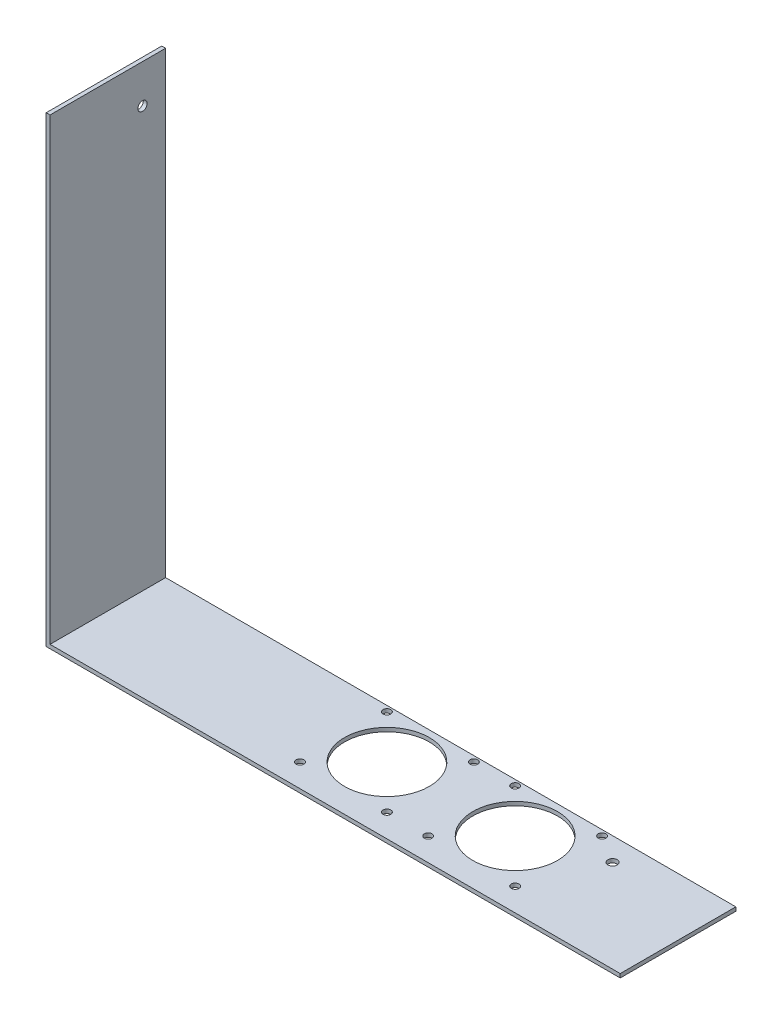
SolidWorks part; units mm, degrees
ref_plane "Front Plane" through (0, 0, 0) normal (0, 0, 1) x (1, 0, 0)
ref_plane "Top Plane" through (0, 0, 0) normal (0, 1, 0) x (1, 0, 0)
ref_plane "Right Plane" through (0, 0, 0) normal (1, 0, 0) x (0, 0, -1)
sketch "Sketch1" plane through (0, 0, 0) normal (0, 0, 1) x (1, 0, 0)
  line L0 (0, 0) -> (0, 381)
  line L5 (0, 381) -> (3.175, 381)
  line L6 (3.175, 381) -> (3.175, 3.175)
  line L7 (3.175, 3.175) -> (473.075, 3.175)
  line L8 (473.075, 3.175) -> (473.075, 0)
  line L9 (473.075, 0) -> (0, 0)
  dimension "D1" = 3.175
  dimension "D2" = 3.175
  dimension "D3" = 381
  dimension "D4" = 473.075
extrude "Boss-Extrude1" add sketch "Sketch1" along normal blind 95.25
sketch "Sketch2" plane through (0, 3.175, 0) normal (0, 1, 0) x (1, 0, 0)
  line L1 (473.075, -95.25) -> (3.175, -95.25) construction
  circle A0 centre (190.119, -4.572) radius 3.175
  circle A1 centre (190.119, -76.2) radius 3.175
  circle A2 centre (261.747, -4.572) radius 3.175
  circle A3 centre (261.747, -76.2) radius 3.175
  circle A4 centre (295.783, -76.2) radius 3.175
  circle A5 centre (295.783, -4.572) radius 3.175
  circle A6 centre (367.411, -76.2) radius 3.175
  circle A7 centre (367.411, -4.572) radius 3.175
  dimension "D3" = 6.35
  dimension "D1" = 6.35
  dimension "D2" = 19.05
  dimension "D4" = 71.628
  dimension "D5" = 71.628
  dimension "D6" = 71.628
  dimension "D7" = 6.35
  dimension "D8" = 6.35
extrude "Cut-Extrude1" cut sketch "Sketch2" against normal blind 152.4
sketch "Sketch4" plane through (0, 0, 0) normal (0, -1, 0) x (1, 0, 0)
  line L0 (473.075, 95.25) -> (473.075, 0) construction
  line L1 (0, 0) -> (473.075, 0) construction
  circle A0 centre (225.933, 40.386) radius 34.925
  circle A1 centre (331.597, 40.386) radius 34.925
  circle A2 centre (390.525, 19.05) radius 3.81
  dimension "D1" = 69.85
  dimension "D2" = 82.55
  dimension "D3" = 19.05
extrude "Cut-Extrude2" cut sketch "Sketch4" against normal blind 381
sketch "Sketch5" plane through (0, 0, 0) normal (-1, 0, 0) x (0, 0, 1)
  line L0 (95.25, 381) -> (0, 381) construction
  line L1 (0, 381) -> (0, 0) construction
  circle A0 centre (19.05, 349.25) radius 3.81
  dimension "D1" = 31.75
  dimension "D2" = 19.05
extrude "Cut-Extrude3" cut sketch "Sketch5" against normal blind 12.7
